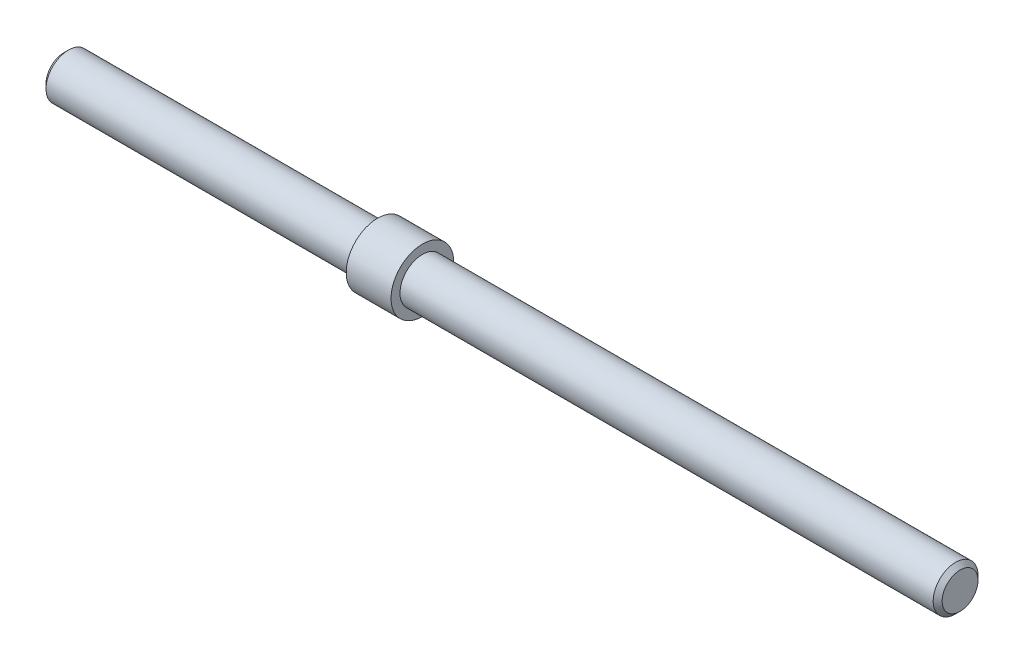
SolidWorks part; units mm, degrees
ref_plane "Front Plane" through (0, 0, 0) normal (0, 0, 1) x (1, 0, 0)
ref_plane "Top Plane" through (0, 0, 0) normal (0, 1, 0) x (1, 0, 0)
ref_plane "Right Plane" through (0, 0, 0) normal (1, 0, 0) x (0, 0, -1)
sketch "Sketch1" plane through (0, 0, 0) normal (1, 0, 0) x (0, 0, -1)
  circle A0 centre (0, 0) radius 5
  dimension "D1" = 10
extrude "Boss-Extrude1" add sketch "Sketch1" along normal blind 200
chamfer "Chamfer1" distance 1 angle 45 2 edges at (200, 0, -5) (0, 0, -5)
sketch "Sketch2" plane through (0, 0, 0) normal (1, 0, 0) x (0, 0, -1)
  circle A0 centre (0, 0) radius 7
  dimension "D1" = 14
extrude "Boss-Extrude2" add sketch "Sketch2" along normal blind 10 from offset 70
